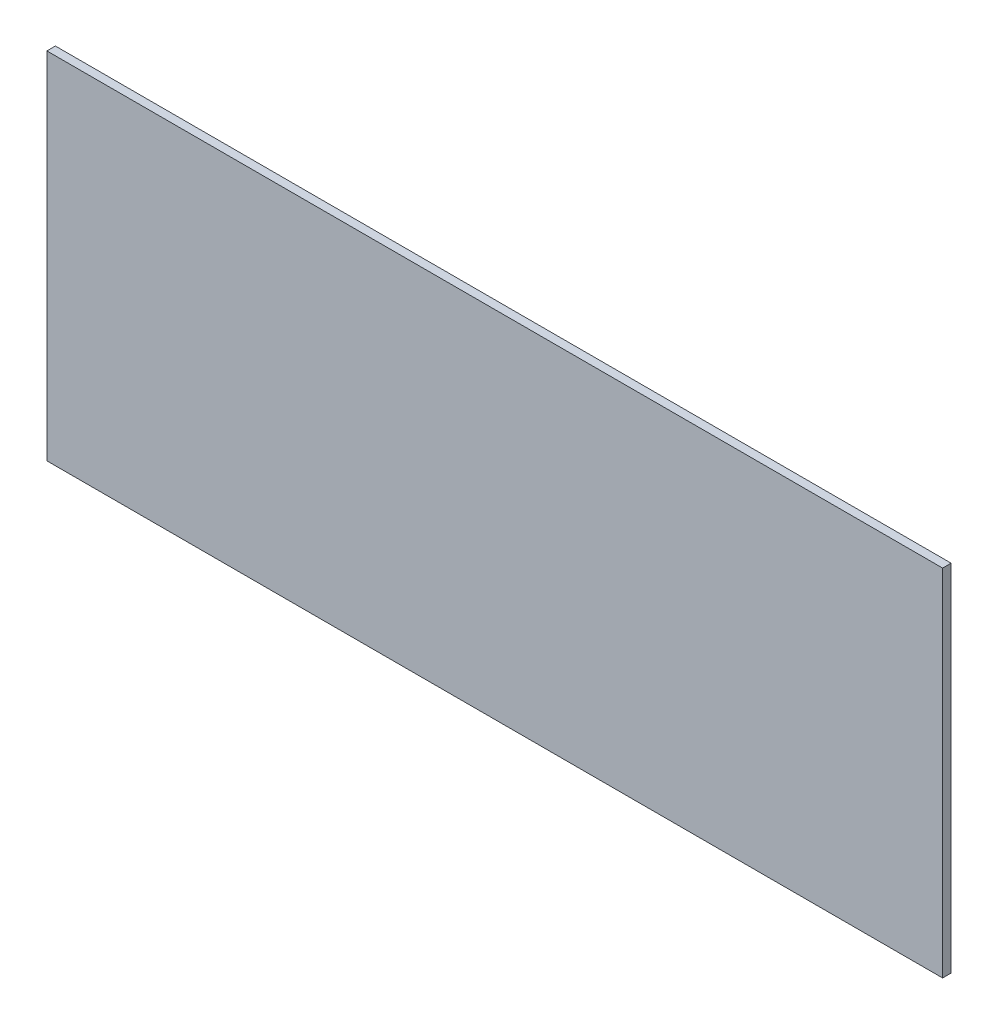
SolidWorks part; units mm, degrees
ref_plane "Front Plane" through (0, 0, 0) normal (0, 0, 1) x (1, 0, 0)
ref_plane "Top Plane" through (0, 0, 0) normal (0, 1, 0) x (1, 0, 0)
ref_plane "Right Plane" through (0, 0, 0) normal (1, 0, 0) x (0, 0, -1)
sketch "Sketch1" plane through (0, 0, 0) normal (0, 0, 1) x (1, 0, 0)
  line L1 (-294.412, -116.688) -> (294.412, -116.688)
  line L2 (-294.412, -116.688) -> (-294.412, 116.688)
  line L3 (-294.412, 116.688) -> (294.412, 116.688)
  line L4 (294.412, -116.688) -> (294.412, 116.688)
  line L5 (-294.412, -116.688) -> (294.412, 116.688) construction
  line L6 (-294.412, 116.688) -> (294.412, -116.688) construction
  point P0 (0, 0)
  dimension "D1" = 588.824
  dimension "D2" = 233.376
extrude "Boss-Extrude1" add sketch "Sketch1" along normal blind 5.588
